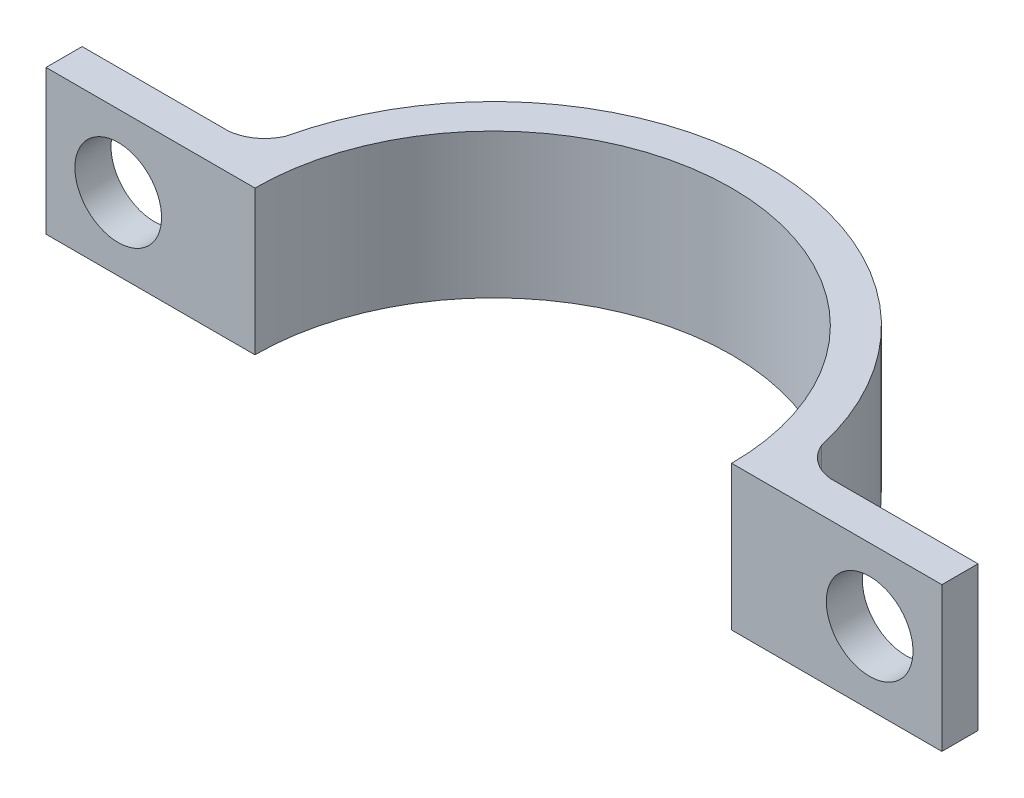
SolidWorks part; units mm, degrees
material "6061 Alloy"
ref_plane "Front Plane" through (0, 0, 0) normal (0, 0, 1) x (1, 0, 0)
ref_plane "Top Plane" through (0, 0, 0) normal (0, 1, 0) x (1, 0, 0)
ref_plane "Right Plane" through (0, 0, 0) normal (1, 0, 0) x (0, 0, -1)
sketch "Sketch1" plane through (0, 0, 0) normal (0, 1, 0) x (1, 0, 0)
  line L0 (-14.7027, -10.0527) -> (-29.1654, -10.0527)
  line L1 (18.2973, -10.0527) -> (32.8499, -10.0527)
  line L2 (-19.0446, -7.5527) -> (-29.1654, -7.5527)
  line L3 (22.6392, -7.5527) -> (32.8499, -7.5527)
  line L4 (-29.1654, -7.5527) -> (-29.1654, -10.0527)
  line L5 (32.8499, -7.5527) -> (32.8499, -10.0527)
  line L6 (1.7973, 6.9473) -> (1.7973, -10.0527) construction
  arc A0 (18.2973, -10.0527) -> (-14.7027, -10.0527) centre (1.7973, -10.0527) ccw
  arc A1 (20.3265, -5.8491) -> (-16.7319, -5.8491) centre (1.7973, -10.0527) ccw
  arc A2 (22.6392, -7.5527) -> (20.3265, -5.8491) centre (22.9029, -4.773) cw
  arc A3 (-19.0446, -7.5527) -> (-16.7319, -5.8491) centre (-19.3084, -4.773) ccw
extrude "Boss-Extrude1" add sketch "Sketch1" along normal blind 10
sketch "Sketch2" plane through (0, 0, 7.5527) normal (0, 0, -1) x (-1, 0, 0)
  line L0 (-32.8499, 0) -> (-32.8499, 5) construction
  line L1 (-32.8499, 10) -> (-32.8499, 0) construction
  line L2 (-32.8499, 5) -> (-27.8499, 5) construction
  line L3 (29.1654, 5) -> (24.1654, 5) construction
  line L4 (29.1654, 10) -> (29.1654, 0) construction
  circle A0 centre (24.1654, 5) radius 3
  circle A1 centre (-27.8499, 5) radius 3
extrude "Cut-Extrude1" cut sketch "Sketch2" against normal blind 8
